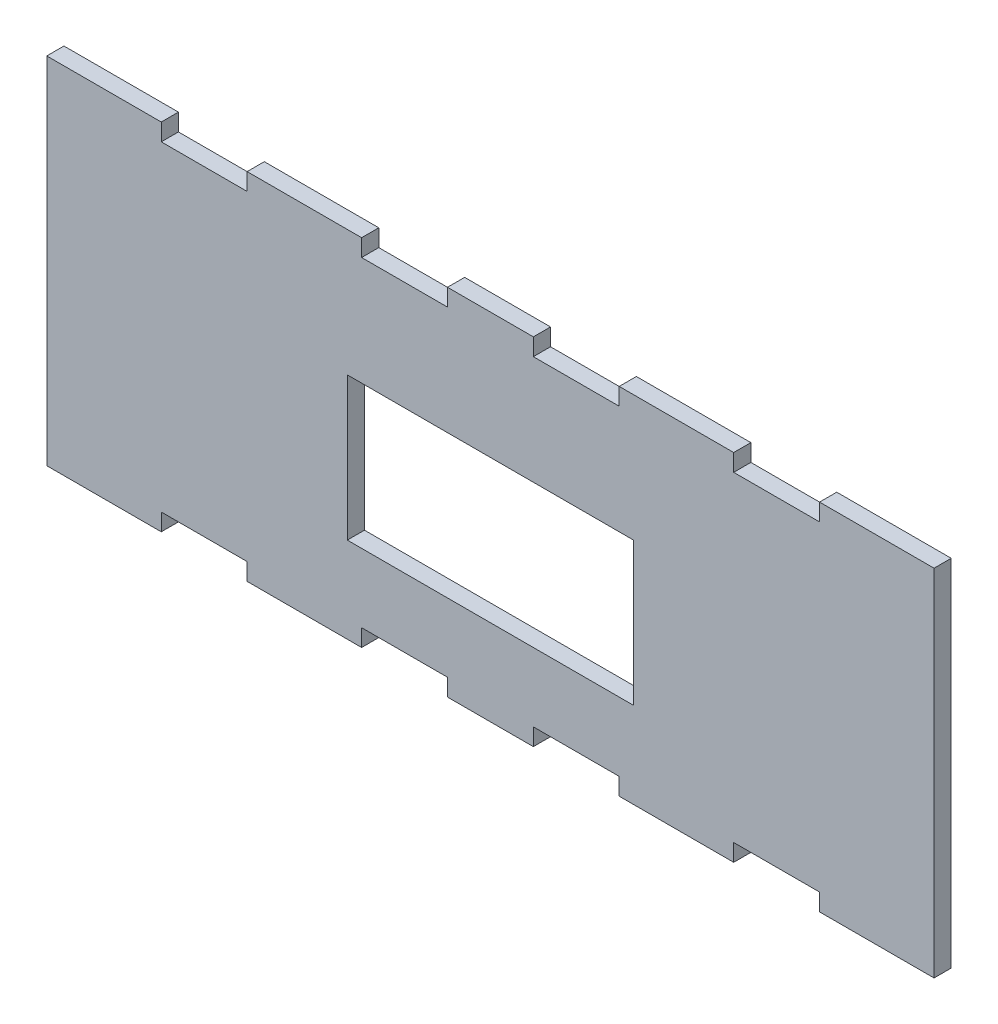
SolidWorks part; units mm, degrees
ref_plane "Přední rovina" through (0, 0, 0) normal (0, 0, 1) x (1, 0, 0)
ref_plane "Horní rovina" through (0, 0, 0) normal (0, 1, 0) x (1, 0, 0)
ref_plane "Pravá rovina" through (0, 0, 0) normal (1, 0, 0) x (0, 0, -1)
sketch "Skica1" plane through (0, 0, 0) normal (0, 0, 1) x (1, 0, 0)
  line L0 (20, 3) -> (35, 3)
  line L1 (0, 0) -> (20, 0)
  line L2 (0, 0) -> (0, 62)
  line L4 (77.5, 0) -> (77.5, 15)
  line L5 (20, 3) -> (20, 0)
  line L6 (35, 3) -> (35, 0)
  line L7 (55, 3) -> (55, 0)
  line L8 (70, 3) -> (70, 0)
  line L9 (35, 0) -> (55, 0)
  line L10 (70, 0) -> (77.5, 0)
  line L11 (55, 3) -> (70, 3)
  line L12 (52.5, 31) -> (-65.3238, 31) construction
  line L13 (20, 59) -> (20, 62)
  line L14 (0, 62) -> (20, 62)
  line L15 (70, 62) -> (77.5, 62)
  line L16 (70, 59) -> (70, 62)
  line L17 (55, 59) -> (70, 59)
  line L18 (55, 59) -> (55, 62)
  line L19 (35, 62) -> (55, 62)
  line L20 (35, 59) -> (35, 62)
  line L21 (20, 59) -> (35, 59)
  line L22 (77.5, 40) -> (52.5, 40)
  line L23 (52.5, 40) -> (52.5, 15)
  line L24 (52.5, 15) -> (77.5, 15)
  line L26 (77.5, 40) -> (77.5, 62)
  dimension "D1" = 20
  dimension "D2" = 15
  dimension "D3" = 20
  dimension "D4" = 3
  dimension "D5" = 15
  dimension "D6" = 62
  dimension "D7" = 77.5
  dimension "D8" = 15
  dimension "D9" = 25
  dimension "D10" = 25
extrude "Přidat vysunutím1" add sketch "Skica1" along normal blind 3
mirror "Zrcadlit1" about plane through (77.5, 0, 3) normal (-1, 0, 0) of "Přidat vysunutím1"
